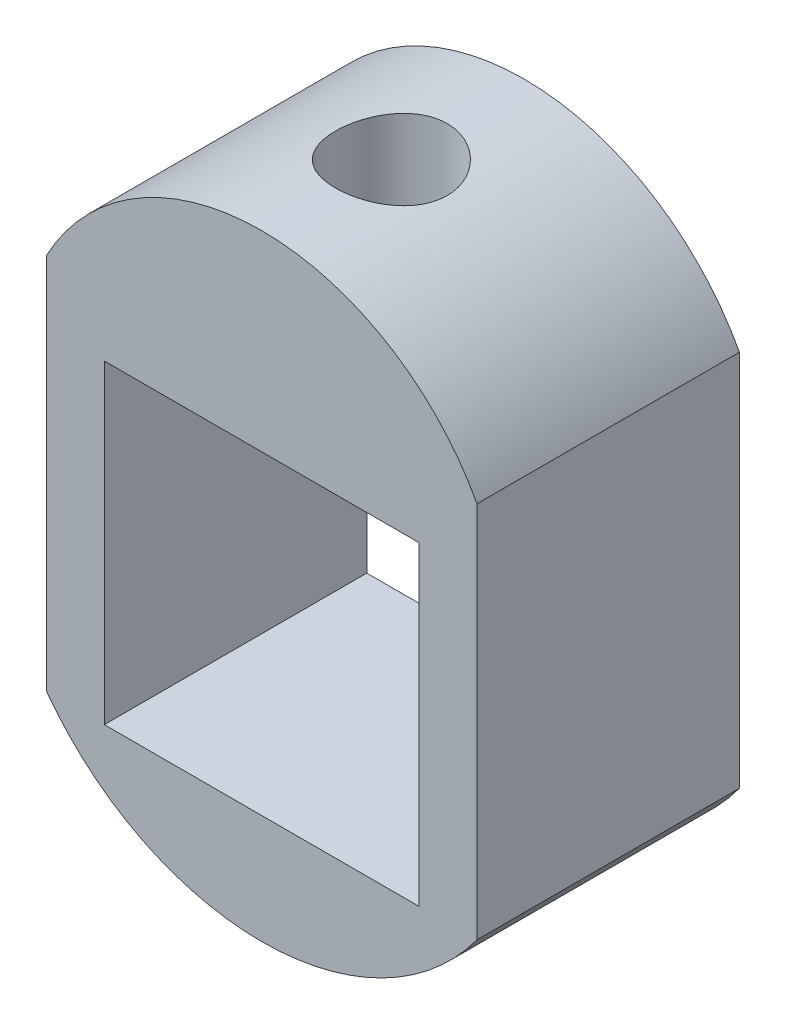
SolidWorks part; units mm, degrees
ref_plane "Front Plane" through (0, 0, 0) normal (0, 0, 1) x (1, 0, 0)
ref_plane "Top Plane" through (0, 0, 0) normal (0, 1, 0) x (1, 0, 0)
ref_plane "Right Plane" through (0, 0, 0) normal (1, 0, 0) x (0, 0, -1)
sketch "Sketch3" plane through (0, 0, 0) normal (0, 0, 1) x (1, 0, 0)
  line L0 (0, -6.35) -> (0, -8.89) construction
  line L1 (-3.81, -6.35) -> (3.81, -6.35)
  line L2 (-3.81, -6.35) -> (-3.81, 1.27)
  line L3 (-3.81, 1.27) -> (3.81, 1.27)
  line L4 (3.81, -6.35) -> (3.81, 1.27)
  line L5 (-3.81, -6.35) -> (3.81, 1.27) construction
  line L6 (-3.81, 1.27) -> (3.81, -6.35) construction
  line L7 (-5.207, 2.7861) -> (-5.207, -6.35)
  line L9 (5.207, 2.7861) -> (5.207, -6.35)
  line L10 (0, 10.9855) -> (0, -10.9855) construction
  line L11 (-5.207, -1.782) -> (5.207, -1.782) construction
  circle A0 centre (0, 0) radius 10.9855 construction
  arc A1 (-5.207, 2.7861) -> (5.207, 2.7861) centre (0, 0) cw
  arc A2 (-5.207, -6.35) -> (5.207, -6.35) centre (0, -2.54) ccw
  point P3 (0, -2.54)
  point P20 (0, -1.782)
  point P22 (0, 5.9055)
  dimension "D1" = 21.971
  dimension "D6" = 10.414
  dimension "D7" = 5.08
  dimension "D2" = 2.54
  dimension "D3" = 7.62
  dimension "D4" = 7.62
  dimension "D5" = 2.54
extrude "Boss-Extrude2" add sketch "Sketch3" along normal blind 6.35
ref_plane "Plane1" through (0, 5.9055, 0) normal (0, 1, 0) x (1, 0, 0)
sketch "Sketch6" plane through (0, 5.9055, 0) normal (0, 1, 0) x (1, 0, 0)
  line L0 (0, 0) -> (0, -6.4287) construction
  circle A0 centre (0, -3.2143) radius 1.3526
  point P3 (0, -3.2143)
  dimension "D1" = 2.7051
extrude "Cut-Extrude1" cut sketch "Sketch6" against normal blind 3.81
ref_plane "Plane2" through (0, -8.992, 0) normal (0, -1, 0) x (-1, 0, 0)
sketch "Sketch7" plane through (0, -8.992, 0) normal (0, -1, 0) x (-1, 0, 0)
  line L0 (0, -6.35) -> (0, 0) construction
  line L1 (-5.207, -6.35) -> (5.207, -6.35) construction
  circle A0 centre (0, -3.175) radius 1.3526
  point P3 (0, -3.175)
  dimension "D1" = 2.7051
extrude "Cut-Extrude2" cut sketch "Sketch7" against normal blind 2.54
sketch "Sketch8" plane through (0, 5.9055, 0) normal (0, 1, 0) x (1, 0, 0)
  point P0 (0, -3.2143)
